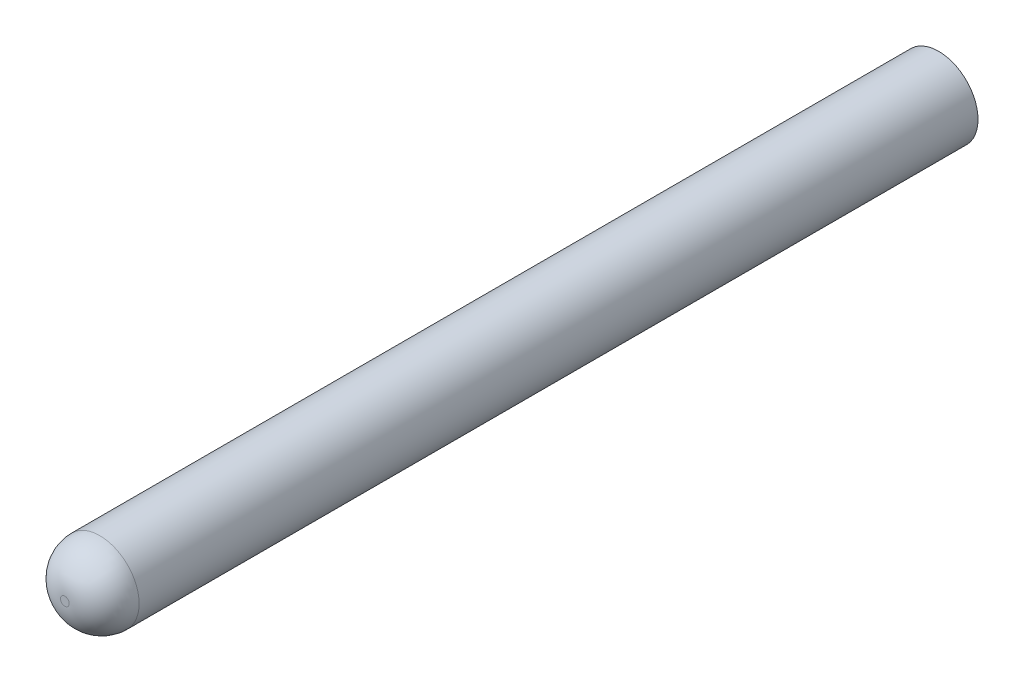
SolidWorks part; units mm, degrees
ref_plane "前视基准面" through (0, 0, 0) normal (0, 0, 1) x (1, 0, 0)
ref_plane "上视基准面" through (0, 0, 0) normal (0, 1, 0) x (1, 0, 0)
ref_plane "右视基准面" through (0, 0, 0) normal (1, 0, 0) x (0, 0, -1)
sketch "草图1" plane through (0, 0, 0) normal (0, 0, 1) x (1, 0, 0)
  circle A0 centre (0, 0) radius 4.5
  dimension "D1" = 9
extrude "凸台-拉伸1" add sketch "草图1" along normal blind 100
fillet "圆角3" radius 4 1 edges at (4.5, 0, 100)
